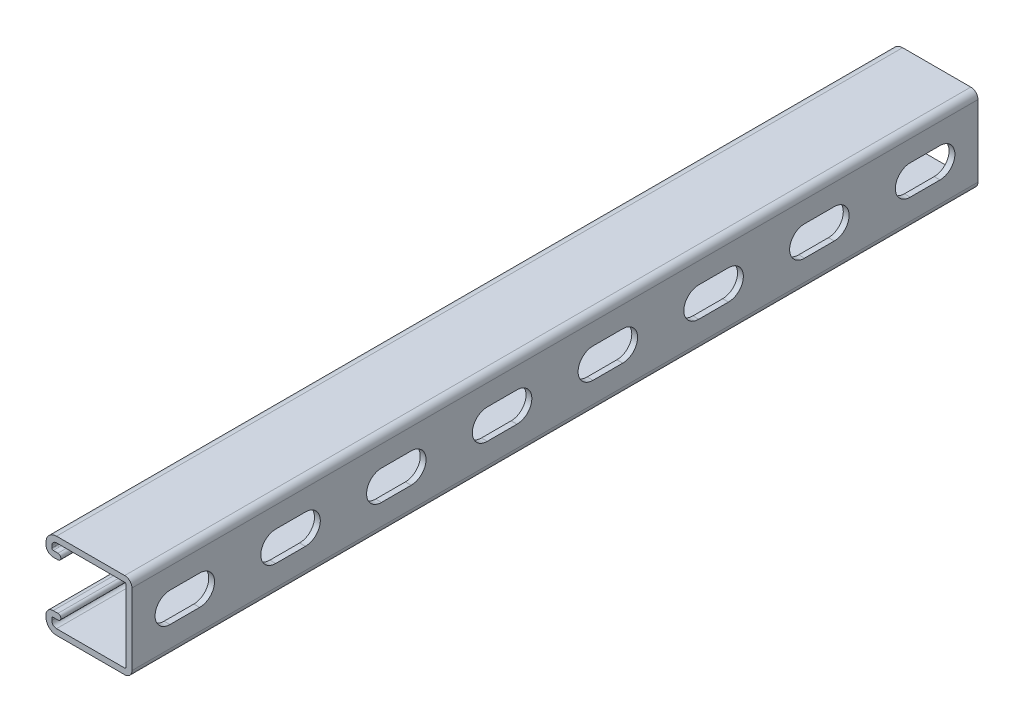
SolidWorks part; units mm, degrees
ref_plane "Front Plane" through (0, 0, 0) normal (0, 0, 1) x (1, 0, 0)
ref_plane "Top Plane" through (0, 0, 0) normal (0, 1, 0) x (1, 0, 0)
ref_plane "Right Plane" through (0, 0, 0) normal (1, 0, 0) x (0, 0, -1)
sketch "Sketch1" plane through (0, 0, 0) normal (0, 0, 1) x (1, 0, 0)
  line L0 (0, 0) -> (-41.275, 0) construction
  line L3 (-41.275, 20.6375) -> (0, 20.6375) construction
  line L4 (-41.275, 20.6375) -> (-41.275, -20.6375) construction
  line L5 (-41.275, -20.6375) -> (0, -20.6375) construction
  line L6 (0, 20.6375) -> (0, -20.6375) construction
  line L7 (-36.2267, 20.6375) -> (-3.4607, 20.6375)
  line L8 (0, 17.1767) -> (0, -17.1767)
  line L9 (-2.794, -17.1767) -> (-2.794, 17.1767)
  line L10 (-3.4608, 17.8435) -> (-36.2267, 17.8435)
  line L11 (-41.275, 15.5892) -> (-41.275, 14.5732)
  line L12 (-37.8142, 11.1125) -> (-35.5346, 11.1125)
  line L14 (-35.5346, 13.9065) -> (-37.8142, 13.9065)
  line L15 (-38.481, 14.5732) -> (-38.481, 15.5892)
  line L16 (-38.481, -14.5733) -> (-38.481, -15.5893)
  line L17 (-35.5346, -13.9065) -> (-37.8142, -13.9065)
  line L18 (-37.8142, -11.1125) -> (-35.5346, -11.1125)
  line L19 (-41.275, -15.5893) -> (-41.275, -14.5733)
  line L20 (-3.4607, -17.8435) -> (-36.2267, -17.8435)
  line L21 (-36.2267, -20.6375) -> (-3.4607, -20.6375)
  line L22 (-2.794, -20.6375) -> (-2.794, 20.6375) construction
  arc A1 (0, 17.1767) -> (-3.4607, 20.6375) centre (-3.4607, 17.1767) ccw
  arc A2 (-2.794, 17.1767) -> (-3.4608, 17.8435) centre (-3.4607, 17.1767) ccw
  arc A4 (-36.2267, 20.6375) -> (-41.275, 15.5892) centre (-36.2267, 15.5892) ccw
  arc A5 (-41.275, 14.5732) -> (-37.8142, 11.1125) centre (-37.8142, 14.5732) ccw
  arc A6 (-35.5346, 11.1125) -> (-35.5346, 13.9065) centre (-35.5346, 12.5095) ccw
  arc A7 (-37.8142, 13.9065) -> (-38.481, 14.5732) centre (-37.8142, 14.5732) cw
  arc A8 (-38.481, 15.5892) -> (-36.2267, 17.8435) centre (-36.2267, 15.5892) cw
  arc A9 (-38.481, -15.5893) -> (-36.2267, -17.8435) centre (-36.2267, -15.5893) ccw
  arc A10 (-37.8142, -13.9065) -> (-38.481, -14.5733) centre (-37.8142, -14.5733) ccw
  arc A11 (-35.5346, -11.1125) -> (-35.5346, -13.9065) centre (-35.5346, -12.5095) cw
  arc A12 (-41.275, -14.5733) -> (-37.8142, -11.1125) centre (-37.8142, -14.5733) cw
  arc A13 (-36.2267, -20.6375) -> (-41.275, -15.5893) centre (-36.2267, -15.5893) cw
  arc A14 (-2.794, -17.1767) -> (-3.4607, -17.8435) centre (-3.4607, -17.1767) cw
  arc A15 (0, -17.1767) -> (-3.4607, -20.6375) centre (-3.4607, -17.1767) cw
  point P24 (0, 20.6375)
  point P65 (-2.794, 0)
  dimension "D1" = 3.4608
  dimension "D2" = 5.0482
  dimension "D3" = 3.4608
  dimension "Ht." = 41.275
  dimension "Wd." = 41.275
  dimension "Thk." = 2.794
  dimension "D4" = 9.525
  dimension "D5" = 7.1374
extrude "Boss-Extrude1" add sketch "Sketch1" against normal blind 406.4
sketch "Sketch3" plane through (0, 0, 0) normal (1, 0, 0) x (0, 0, -1)
  line L0 (0, 0) -> (406.4, 0) construction
  point P2 (101.6, 0)
  point P3 (304.8, 0)
  dimension "D1" = 101.6
  dimension "D2" = 101.6
  dimension "D3" = 406.4
sketch "Sketch2" plane through (0, 0, 0) normal (1, 0, 0) x (0, 0, -1)
  line L0 (18.2562, 0) -> (32.5437, 0) construction
  line L1 (18.2562, 7.1437) -> (32.5437, 7.1437)
  line L2 (18.2562, -7.1437) -> (32.5437, -7.1437)
  line L3 (18.2562, 0) -> (0, 0) construction
  line L4 (25.4, 0) -> (76.2, 0) construction
  line L5 (0, -17.1767) -> (0, 17.1767) construction
  arc A0 (18.2562, 7.1437) -> (18.2562, -7.1437) centre (18.2562, 0) ccw
  arc A1 (32.5437, -7.1437) -> (32.5437, 7.1437) centre (32.5437, 0) ccw
  point P3 (25.4, 0)
  dimension "Hole to End" = 11.1125
  dimension "D2" = 25.4
extrude "Cut-Extrude1" cut sketch "Sketch2" against normal up to vertex (2.794 mm away) up to point (-2.794, 0, 0)
pattern_linear "LPattern1" count 8 spacing 50.8 along (0, 0, -1) of "Cut-Extrude1"
equation "\"D1@LPattern1\" = \"Slot Ctr.@Sketch2\""
equation "\"Hole Count@LPattern1\" = \"Lg.@Boss-Extrude1\" / \"D1@LPattern1\""
equation "\"D3@Sketch3\" = \"Lg.@Boss-Extrude1\""
